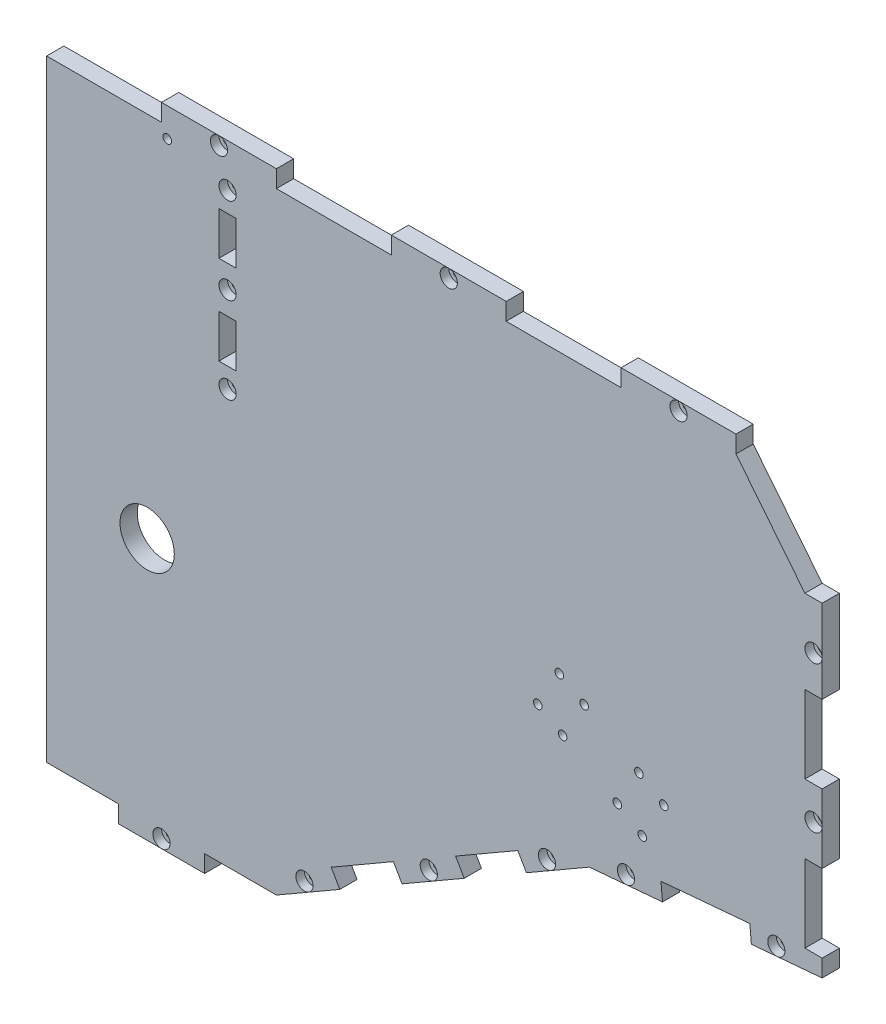
SolidWorks part; units mm, degrees
ref_plane "Plan de face" through (0, 0, 0) normal (0, 0, 1) x (1, 0, 0)
ref_plane "Plan de dessus" through (0, 0, 0) normal (0, 1, 0) x (1, 0, 0)
ref_plane "Plan de droite" through (0, 0, 0) normal (1, 0, 0) x (0, 0, -1)
sketch "Esquisse1" plane through (0, 0, 0) normal (0, 0, 1) x (1, 0, 0)
  line L1 (135, -106.5) -> (-135, -106.5)
  line L2 (135, -106.5) -> (135, 106.5)
  line L3 (135, 106.5) -> (-135, 106.5)
  line L4 (-135, -106.5) -> (-135, 106.5)
  line L5 (135, -106.5) -> (-135, 106.5) construction
  line L6 (135, 106.5) -> (-135, -106.5) construction
  point P0 (0, 0)
extrude "Boss.-Extru.1" add sketch "Esquisse1" along normal blind 6
sketch "Esquisse3" plane through (0, 0, 6) normal (0, 0, 1) x (1, 0, 0)
  line L0 (-135, -106.5) -> (135, -106.5) construction
  line L1 (-135, 106.5) -> (-135, -106.5) construction
  circle A0 centre (-100, -21.5) radius 9.45
  circle A1 centre (35.99, -3.47) radius 1.5
  circle A2 centre (43.49, 9.52) radius 1.5
  circle A3 centre (44.65, -8.5073) radius 1.5
  circle A4 centre (52.15, 4.4827) radius 1.5
  circle A5 centre (71.2, -6.5173) radius 1.5
  circle A6 centre (63.7, -19.5073) radius 1.5
  circle A7 centre (72.36, -24.9627) radius 1.5
  circle A8 centre (79.86, -11.9727) radius 1.5
  dimension "D1" = 85
  dimension "D3" = 3
  dimension "D4" = 170.99
  dimension "D5" = 103.03
  dimension "D6" = 3
  dimension "D7" = 7.5
  dimension "D8" = 3
  dimension "D9" = 3
  dimension "D10" = 12.99
  dimension "D19" = 18.9
  dimension "D11" = 8.66
  dimension "D12" = 8.66
  dimension "D13" = 12.99
  dimension "D14" = 19.05
  dimension "D15" = 11
  dimension "D16" = 7.5
  dimension "D17" = 12.99
  dimension "D18" = 3
  dimension "D20" = 3
  dimension "D21" = 8.66
  dimension "D22" = 3
  dimension "D23" = 8.66
  dimension "D24" = 3
  dimension "D25" = 12.99
  dimension "D2" = 35
extrude "Enlèv. mat.-Extru.1" cut sketch "Esquisse3" against normal blind 10
sketch "Esquisse5" plane through (0, 0, 6) normal (0, 0, 1) x (1, 0, 0)
  line L0 (53.9637, -43.5898) -> (135, -36.5)
  line L1 (53.9637, -43.5898) -> (-55, -106.5)
  line L3 (135, -106.5) -> (135, 106.5) construction
  line L4 (-135, -106.5) -> (135, -106.5) construction
  dimension "D1" = 80
  dimension "D2" = 95
  dimension "D3" = 0
  dimension "D4" = 150
  dimension "D5" = 70
  dimension "D6" = 0
extrude "Enlèv. mat.-Extru.11" cut sketch "Esquisse5" against normal through all and the other way through all
sketch "Esquisse7" plane through (0, 0, 6) normal (0, 0, 1) x (1, 0, 0)
  line L0 (135, -36.5) -> (135, 106.5) construction
  line L1 (135, 106.5) -> (129, 106.5)
  line L2 (135, 106.5) -> (135, 76.5)
  line L3 (135, 76.5) -> (129, 76.5)
  line L4 (129, 106.5) -> (129, 76.5)
  line L6 (135, -3.5) -> (129, -3.5)
  line L7 (135, -3.5) -> (135, -30.5)
  line L8 (135, -30.5) -> (129, -30.5)
  line L9 (135, 20.5) -> (129, 20.5)
  line L10 (135, 20.5) -> (135, 47.5)
  line L11 (135, 47.5) -> (129, 47.5)
  line L12 (129, 20.5) -> (129, 47.5)
  line L13 (129, -3.5) -> (129, -30.5)
  dimension "D1" = 24
  dimension "D2" = 29
  dimension "D3" = 27
  dimension "D4" = 30
  dimension "D5" = 27
  dimension "D6" = 6
  dimension "D7" = 6
extrude "Enlèv. mat.-Extru.13" cut sketch "Esquisse7" against normal blind 10
sketch "Esquisse8" plane through (0, 106.5, 0) normal (0, 1, 0) x (1, 0, 0)
  line L0 (129, -6) -> (-135, -6) construction
  line L1 (105, -6) -> (65, -6)
  line L2 (105, -6) -> (105, 0)
  line L3 (105, 0) -> (65, 0)
  line L4 (65, -6) -> (65, 0)
  line L5 (129, 0) -> (-135, 0) construction
  line L8 (25, -6) -> (-15, -6)
  line L9 (25, -6) -> (25, 0)
  line L10 (25, 0) -> (-15, 0)
  line L11 (-15, -6) -> (-15, 0)
  line L12 (-55, -6) -> (-95, -6)
  line L13 (-55, -6) -> (-55, 0)
  line L14 (-55, 0) -> (-95, 0)
  line L15 (-95, -6) -> (-95, 0)
  dimension "D1" = 40
  dimension "D2" = 40
  dimension "D3" = 40
  dimension "D4" = 40
  dimension "D5" = 40
  dimension "D6" = 40
extrude "Boss.-Extru.2" add sketch "Esquisse8" along normal blind 6
sketch "Esquisse9" plane through (0, 0, 0) normal (0, 0, -1) x (-1, 0, 0)
  line L0 (-110.35, -38.6566) -> (-79.4137, -41.3632)
  line L1 (-78.8908, -35.386) -> (-109.8271, -32.6794)
  line L2 (-53.9637, -43.5898) -> (-135, -36.5) construction
  line L3 (-79.4137, -41.3632) -> (-78.8908, -35.386)
  line L4 (-109.8271, -32.6794) -> (-110.35, -38.6566)
  dimension "D1" = 25.45
  dimension "D2" = 24.65
  dimension "D3" = 6
  dimension "D4" = 6
extrude "Enlèv. mat.-Extru.14" cut sketch "Esquisse9" against normal blind 10
sketch "Esquisse10" plane through (0, 0, 0) normal (0, 0, -1) x (-1, 0, 0)
  line L0 (-32.0356, -56.25) -> (-10.3849, -68.75)
  line L1 (55, -106.5) -> (-53.9637, -43.5898) construction
  line L2 (-10.3849, -68.75) -> (-7.3849, -63.5538)
  line L3 (-7.3849, -63.5538) -> (-29.0356, -51.0538)
  line L4 (-29.0356, -51.0538) -> (-32.0356, -56.25)
  line L5 (11.2657, -81.25) -> (32.9164, -93.75)
  line L6 (32.9164, -93.75) -> (35.9164, -88.5538)
  line L7 (35.9164, -88.5538) -> (14.2657, -76.0538)
  line L8 (14.2657, -76.0538) -> (11.2657, -81.25)
  dimension "D1" = 25
  dimension "D2" = 25
  dimension "D3" = 25
  dimension "D4" = 25.5
  dimension "D5" = 6
  dimension "D6" = 6
extrude "Enlèv. mat.-Extru.15" cut sketch "Esquisse10" against normal blind 6
sketch "Esquisse11" plane through (0, 0, 0) normal (0, 0, -1) x (-1, 0, 0)
  line L0 (135, -106.5) -> (55, -106.5) construction
  line L1 (69, 59.5) -> (75, 59.5)
  line L2 (69, 59.5) -> (69, 44.5)
  line L3 (69, 44.5) -> (75, 44.5)
  line L4 (75, 59.5) -> (75, 44.5)
  line L5 (135, 106.5) -> (135, -106.5) construction
  line L7 (69, 90.5) -> (75, 90.5)
  line L8 (69, 90.5) -> (69, 75.5)
  line L9 (69, 75.5) -> (75, 75.5)
  line L10 (75, 90.5) -> (75, 75.5)
  dimension "D1" = 6
  dimension "D2" = 15
  dimension "D3" = 151
  dimension "D4" = 60
  dimension "D5" = 15
  dimension "D6" = 16
extrude "Enlèv. mat.-Extru.16" cut sketch "Esquisse11" against normal blind 10
sketch "Esquisse14" plane through (0, -106.5, 0) normal (0, -1, 0) x (1, 0, 0)
  line L0 (-135, 0) -> (-55, 0) construction
  line L1 (-110, 0) -> (-80, 0)
  line L2 (-110, 0) -> (-110, 6)
  line L3 (-110, 6) -> (-80, 6)
  line L4 (-80, 0) -> (-80, 6)
  line L5 (-135, 6) -> (-55, 6) construction
  dimension "D1" = 30
  dimension "D2" = 25
extrude "Boss.-Extru.3" add sketch "Esquisse14" along normal blind 6
sketch "Esquisse15" plane through (0, 0, 6) normal (0, 0, 1) x (1, 0, 0)
  line L0 (105, 106.5) -> (129, 106.5)
  line L1 (129, 106.5) -> (129, 76.5)
  line L2 (129, 76.5) -> (105, 106.5)
extrude "Enlèv. mat.-Extru.18" cut sketch "Esquisse15" against normal through all
sketch "Esquisse17" plane through (0, 0, 6) normal (0, 0, 1) x (1, 0, 0)
  line L0 (-95, 112.5) -> (-55, 112.5) construction
  line L1 (135, 47.5) -> (135, 76.5) construction
  line L2 (-11.2657, -81.25) -> (10.3849, -68.75) construction
  line L3 (110.35, -38.6566) -> (135, -36.5) construction
  line L4 (-95, 112.5) -> (-95, 106.5) construction
  line L5 (-15, 112.5) -> (-15, 106.5) construction
  line L6 (65, 112.5) -> (65, 106.5) construction
  line L7 (135, -3.5) -> (129, -3.5) construction
  line L8 (135, 47.5) -> (129, 47.5) construction
  line L9 (-14.2657, -76.0538) -> (-11.2657, -81.25) construction
  line L10 (53.9637, -43.5898) -> (79.4137, -41.3632) construction
  line L11 (-55, -106.5) -> (-32.9164, -93.75) construction
  line L12 (78.8908, -35.386) -> (79.4137, -41.3632) construction
  line L13 (-32.9164, -93.75) -> (-35.9164, -88.5538) construction
  line L14 (-80, -112.5) -> (-110, -112.5) construction
  line L15 (-110, -112.5) -> (-110, -106.5) construction
  line L16 (-15, 112.5) -> (25, 112.5) construction
  line L17 (65, 112.5) -> (105, 112.5) construction
  line L18 (135, -3.5) -> (135, 20.5) construction
  line L19 (110.35, -38.6566) -> (109.8271, -32.6794) construction
  line L20 (29.0356, -51.0538) -> (32.0356, -56.25) construction
  line L21 (32.0356, -56.25) -> (53.9637, -43.5898) construction
  line L22 (-75, 90.5) -> (-75, 75.5) construction
  line L23 (-69, 90.5) -> (-75, 90.5) construction
  line L24 (-75, 75.5) -> (-69, 75.5) construction
  line L25 (-75, 59.5) -> (-75, 44.5) construction
  line L26 (-75, 44.5) -> (-69, 44.5) construction
  circle A0 centre (-75, 109.5) radius 2.995
  circle A1 centre (5, 109.5) radius 2.995
  circle A2 centre (85, 109.5) radius 2.995
  circle A3 centre (132, 60) radius 2.995
  circle A4 centre (132, 9) radius 2.995
  circle A5 centre (-1.9404, -72.4019) radius 2.995
  circle A6 centre (119.0543, -34.8836) radius 2.995
  circle A7 centre (66.6998, -39.464) radius 2.995
  circle A8 centre (-45.2417, -97.4019) radius 2.995
  circle A9 centre (-95, -109.5) radius 2.995
  circle A10 centre (39.1958, -48.6519) radius 2.995
  circle A11 centre (-72, 67.5) radius 3
  circle A12 centre (-72, 37.5) radius 3
  circle A13 centre (-72, 97.5) radius 2.995
  point P24 (-15, 109.5)
  point P27 (65, 109.5)
  point P34 (-12.7657, -78.6519)
  point P48 (79.1523, -38.3746)
  point P49 (-34.4164, -91.1519)
  point P64 (110.0885, -35.668)
  dimension "D1" = 5.99
  dimension "D3" = 5.99
  dimension "D4" = 5.99
  dimension "D5" = 5.99
  dimension "D7" = 5.99
  dimension "D10" = 5.99
  dimension "D11" = 5.99
  dimension "D18" = 5.99
  dimension "D19" = 5.99
  dimension "D24" = 5.99
  dimension "D25" = 3
  dimension "D26" = 15
  dimension "D27" = 3
  dimension "D28" = 3
  dimension "D29" = 3
  dimension "D30" = 9
  dimension "D31" = 5.99
  dimension "D32" = 10
  dimension "D33" = 3
  dimension "D34" = 5.99
  dimension "D35" = 3
  dimension "D36" = 7
  dimension "D37" = 6
  dimension "D38" = 3
  dimension "D39" = 8
  dimension "D40" = 6
  dimension "D41" = 3
  dimension "D42" = 7
  dimension "D2" = 3
  dimension "D6" = 3
  dimension "D8" = 3
  dimension "D9" = 3
  dimension "D12" = 20
  dimension "D13" = 20
  dimension "D14" = 20
  dimension "D15" = 12.5
  dimension "D16" = 12.5
  dimension "D17" = 12.5
  dimension "D20" = 3
  dimension "D21" = 3
  dimension "D22" = 12.5
  dimension "D23" = 12.5
extrude "Enlèv. mat.-Extru.20" cut sketch "Esquisse17" against normal blind 3
sketch "Esquisse18" plane through (0, 0, 6) normal (0, 0, 1) x (1, 0, 0)
  line L0 (-55, 112.5) -> (-95, 112.5) construction
  line L5 (-135, 106.5) -> (-135, -106.5) construction
  circle A0 centre (-75, 109.5) radius 1.5
  circle A1 centre (5, 109.5) radius 1.5
  circle A2 centre (85, 109.5) radius 1.5
  circle A3 centre (132, 60) radius 1.5
  circle A4 centre (132, 9) radius 1.5
  circle A5 centre (119.0543, -34.8836) radius 1.5
  circle A6 centre (66.6998, -39.464) radius 1.5
  circle A7 centre (-1.9404, -72.4019) radius 1.5
  circle A8 centre (-45.2417, -97.4019) radius 1.5
  circle A9 centre (-72, 97.5) radius 1.5
  circle A10 centre (-72, 67.5) radius 1.5
  circle A11 centre (-72, 37.5) radius 1.5
  circle A12 centre (-95, -109.5) radius 1.5
  circle A13 centre (39.1958, -48.6519) radius 1.5
  circle A14 centre (-93, 102.5) radius 1.5
  dimension "D1" = 3
  dimension "D2" = 3
  dimension "D3" = 3
  dimension "D4" = 3
  dimension "D5" = 3
  dimension "D6" = 3
  dimension "D7" = 3
  dimension "D8" = 3
  dimension "D9" = 3
  dimension "D10" = 3
  dimension "D11" = 3
  dimension "D12" = 3
  dimension "D13" = 3
  dimension "D14" = 3
  dimension "D15" = 3
  dimension "D16" = 10
  dimension "D17" = 42
extrude "Enlèv. mat.-Extru.21" cut sketch "Esquisse18" against normal blind 13
